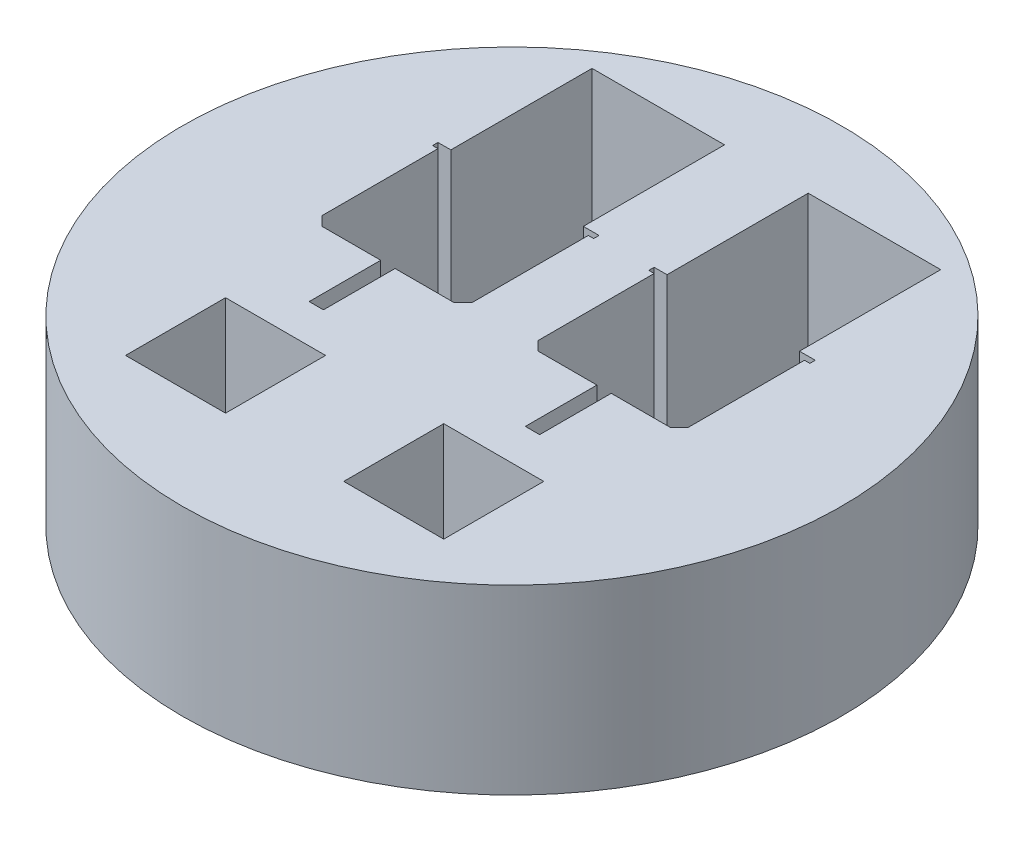
SolidWorks part; units mm, degrees
material "Polyurethane Foam Flexible"
ref_plane "Front Plane" through (0, 0, 0) normal (0, 0, 1) x (1, 0, 0)
ref_plane "Top Plane" through (0, 0, 0) normal (0, 1, 0) x (1, 0, 0)
ref_plane "Right Plane" through (0, 0, 0) normal (1, 0, 0) x (0, 0, -1)
sketch "Sketch1" plane through (0, 0, 0) normal (0, 1, 0) x (1, 0, 0)
  circle A0 centre (0, 0) radius 92.075
  dimension "D1" = 184.15
extrude "Boss-Extrude1" add sketch "Sketch1" along normal blind 50.8
sketch "Sketch4" plane through (0, 0, 0) normal (0, 1, 0) x (1, 0, 0)
  line L0 (0, 0) -> (0, 16.6464) construction
  line L1 (-55.88, 71.12) -> (-5.08, 71.12)
  line L2 (-55.88, 71.12) -> (-55.88, -25.4)
  line L3 (-55.88, -25.4) -> (-5.08, -25.4)
  line L4 (-5.08, 71.12) -> (-5.08, -25.4)
  line L5 (55.88, 71.12) -> (5.08, 71.12)
  line L6 (5.08, 71.12) -> (5.08, -25.4)
  line L7 (55.88, -25.4) -> (5.08, -25.4)
  line L8 (55.88, 71.12) -> (55.88, -25.4)
  dimension "D1" = 5.08
  dimension "D2" = 96.52
  dimension "D3" = 71.12
  dimension "D4" = 50.8
extrude "Cut-Extrude3" [suppressed] cut sketch "Sketch4" along normal up to surface (50.8 mm away)
sketch "Sketch6" plane through (0, 0, 0) normal (0, -1, 0) x (1, 0, 0)
  line L1 (-44.45, -63.5) -> (-16.51, -63.5) construction
  line L2 (-44.45, -63.5) -> (-44.45, -35.56) construction
  line L3 (-44.45, -35.56) -> (-16.51, -35.56) construction
  line L4 (-16.51, -63.5) -> (-16.51, -35.56) construction
  line L5 (0, 0) -> (0, -11.8444) construction
  line L6 (44.45, -63.5) -> (44.45, -35.56) construction
  line L7 (44.45, -63.5) -> (16.51, -63.5) construction
  line L8 (16.51, -63.5) -> (16.51, -35.56) construction
  line L9 (44.45, -35.56) -> (16.51, -35.56) construction
  line L10 (0, 0) -> (-75.2732, 0) construction
  line L11 (44.45, 63.5) -> (16.51, 63.5)
  line L12 (44.45, 63.5) -> (44.45, 35.56)
  line L13 (-44.45, 35.56) -> (-16.51, 35.56)
  line L14 (44.45, 35.56) -> (16.51, 35.56)
  line L15 (16.51, 63.5) -> (16.51, 35.56)
  line L16 (-16.51, 63.5) -> (-16.51, 35.56)
  line L17 (-44.45, 63.5) -> (-16.51, 63.5)
  line L18 (-44.45, 63.5) -> (-44.45, 35.56)
  dimension "D1" = 27.94
  dimension "D2" = 27.94
  dimension "D3" = 35.56
  dimension "D4" = 16.51
extrude "Cut-Extrude4" cut sketch "Sketch6" against normal up to surface (50.8 mm away) up to face at (0, 50.8, 92.075)
sketch "Sketch8" plane through (0, 50.8, 0) normal (0, 1, 0) x (1, 0, 0)
  line L0 (48.6732, 66.9206) -> (48.6732, 31.675)
  line L1 (48.6732, 31.675) -> (53.066, 31.675)
  line L2 (53.066, 31.675) -> (53.066, 30.175)
  line L3 (53.066, 30.175) -> (51.5683, 30.175)
  line L4 (51.5683, 30.175) -> (51.5683, -2.285)
  line L5 (51.5683, -2.285) -> (49.0283, -4.825)
  line L6 (49.0283, -4.825) -> (32.5683, -4.825)
  line L7 (32.5683, -4.825) -> (32.5683, -24.825)
  line L8 (32.5683, -24.825) -> (28.5683, -24.825)
  line L9 (28.5683, -24.825) -> (28.5683, -4.825)
  line L10 (28.5683, -4.825) -> (12.1083, -4.825)
  line L11 (12.1083, -4.825) -> (9.5683, -2.285)
  line L12 (9.5683, -2.285) -> (9.5683, 30.175)
  line L13 (9.5683, 30.175) -> (8.066, 30.175)
  line L14 (8.066, 30.175) -> (8.066, 31.675)
  line L15 (8.066, 31.675) -> (10.8383, 31.675)
  line L16 (11.6589, 66.9206) -> (11.6589, 31.675)
  line L17 (11.6589, 31.675) -> (10.8383, 31.675)
  line L18 (11.6589, 66.9206) -> (11.6589, 71.12)
  line L20 (11.6589, 71.12) -> (48.6732, 71.12)
  line L21 (48.6732, 71.12) -> (48.6732, 66.9206)
  line L22 (-8.8317, -2.285) -> (-11.3717, -4.825)
  line L23 (-11.3717, -4.825) -> (-27.8317, -4.825)
  line L24 (-27.8317, -4.825) -> (-27.8317, -24.825)
  line L25 (-27.8317, -24.825) -> (-31.8317, -24.825)
  line L26 (-31.8317, -24.825) -> (-31.8317, -4.825)
  line L27 (-31.8317, -4.825) -> (-48.2917, -4.825)
  line L28 (-48.2917, -4.825) -> (-50.8317, -2.285)
  line L29 (-50.8317, -2.285) -> (-50.8317, 30.175)
  line L30 (-50.8317, 30.175) -> (-52.334, 30.175)
  line L31 (-52.334, 30.175) -> (-52.334, 31.675)
  line L32 (-52.334, 31.675) -> (-48.7411, 31.675)
  line L33 (-48.7411, 66.9206) -> (-48.7411, 31.675)
  line L34 (-8.8317, -2.285) -> (-8.8317, 30.175)
  line L35 (-8.8317, 30.175) -> (-7.334, 30.175)
  line L36 (-7.334, 30.175) -> (-7.334, 31.675)
  line L37 (-11.7268, 66.9206) -> (-11.7268, 31.675)
  line L38 (-11.7268, 31.675) -> (-7.334, 31.675)
  line L39 (-11.7268, 66.9206) -> (-11.7268, 71.12)
  line L41 (-11.7268, 71.12) -> (-48.7411, 71.12)
  line L42 (-48.7411, 71.12) -> (-48.7411, 66.9206)
extrude "Cut-Extrude5" cut sketch "Sketch8" against normal up to surface (50.8 mm away) up to face at (-30.48, 0, 49.53)
